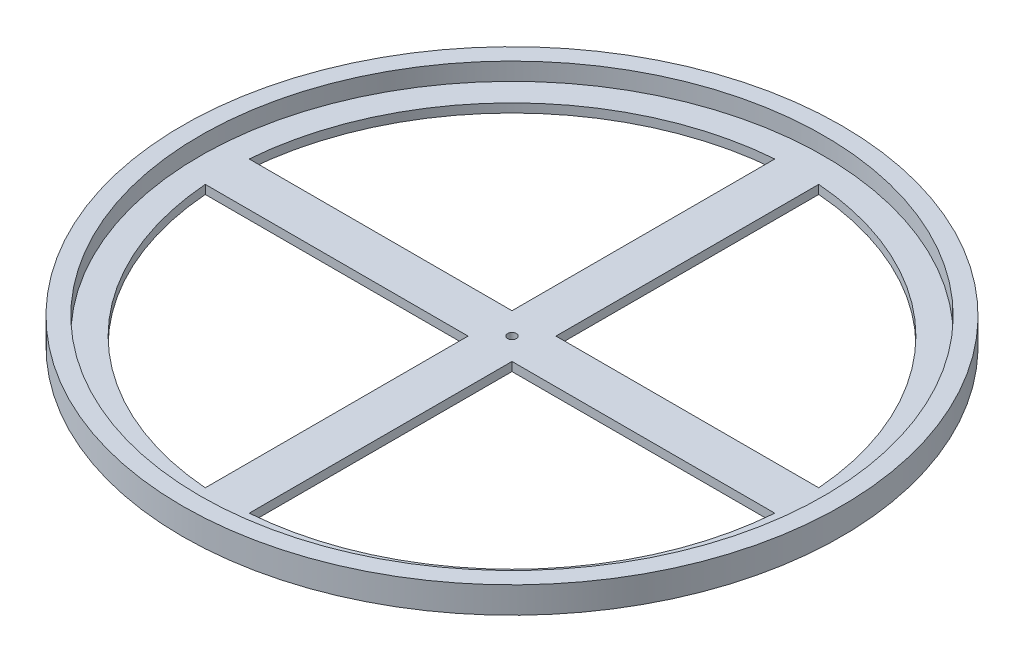
SolidWorks part; units mm, degrees
ref_plane "Front Plane" through (0, 0, 0) normal (0, 0, 1) x (1, 0, 0)
ref_plane "Top Plane" through (0, 0, 0) normal (0, 1, 0) x (1, 0, 0)
ref_plane "Right Plane" through (0, 0, 0) normal (1, 0, 0) x (0, 0, -1)
sketch "Sketch1" plane through (0, 0, 0) normal (0, 1, 0) x (1, 0, 0)
  line L0 (-2.5, 32.4037) -> (-2.5, -32.4037)
  line L1 (2.5, 32.4037) -> (2.5, -32.4037)
  line L2 (-32.4037, 2.5) -> (32.4037, 2.5)
  line L3 (-32.4037, -2.5) -> (32.4037, -2.5)
  circle A0 centre (0, 0) radius 37.5
  circle A1 centre (0, 0) radius 0.5
  circle A2 centre (0, 0) radius 32.5
  dimension "D1" = 1
  dimension "D2" = 75
  dimension "D3" = 65
  dimension "D4" = 5
extrude "Boss-Extrude1" add sketch "Sketch1" along normal blind 1 contours A0 A2 | L1 A2 L0 L2 | L0 A2 L1 L3 | L2 A2 L3 L0 | L3 A2 L2 L1 | L0 L3 L1 L2 A1
sketch "Sketch2" plane through (0, 1, 0) normal (0, 1, 0) x (1, 0, 0)
  circle A0 centre (0, 0) radius 37.5 construction
  circle A1 centre (0, 0) radius 37.5
  circle A2 centre (0, 0) radius 35.5
  dimension "D1" = 71
extrude "Boss-Extrude2" add sketch "Sketch2" along normal blind 2
